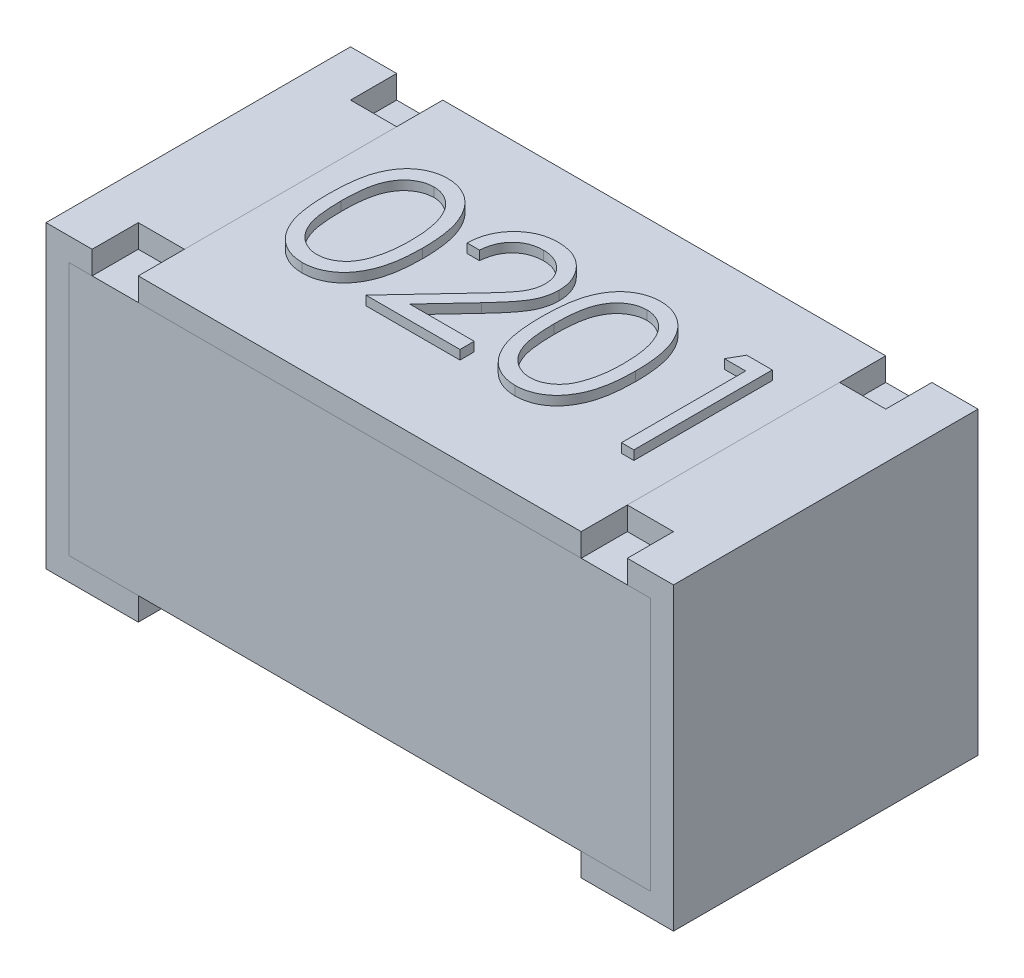
SolidWorks part; units mm, degrees
ref_plane "Front Plane" through (0, 0, 0) normal (0, 0, 1) x (1, 0, 0)
ref_plane "Top Plane" through (0, 0, 0) normal (0, 1, 0) x (1, 0, 0)
ref_plane "Right Plane" through (0, 0, 0) normal (1, 0, 0) x (0, 0, -1)
sketch "Croquis1" plane through (0, 0, 0) normal (0, 1, 0) x (1, 0, 0)
  line L1 (0.315, 0.165) -> (-0.315, 0.165)
  line L2 (0.315, 0.165) -> (0.315, -0.165)
  line L3 (0.315, -0.165) -> (-0.315, -0.165)
  line L4 (-0.315, 0.165) -> (-0.315, -0.165)
  line L5 (0.315, 0.165) -> (-0.315, -0.165) construction
  line L6 (0.315, -0.165) -> (-0.315, 0.165) construction
  point P0 (0, 0)
  dimension "D1" = 0.33
  dimension "D2" = 0.63
extrude "Extruir1" add sketch "Croquis1" along normal blind 0.3
sketch "Croquis2" plane through (0, 0, 0.165) normal (0, 0, 1) x (1, 0, 0)
  line L0 (0.315, 0.3) -> (0.315, 0) construction
  line L1 (-0.315, 0) -> (0.315, 0)
  line L2 (-0.315, 0) -> (-0.315, 0.025)
  line L3 (-0.315, 0.025) -> (0.315, 0.025)
  line L4 (0.315, 0) -> (0.315, 0.025)
  dimension "D1" = 0.025
extrude "Extruir2" cut sketch "Croquis2" against normal through all
sketch "Croquis3" plane through (0, 0, 0.165) normal (0, 0, 1) x (1, 0, 0)
  line L0 (-0.24, 0.325) -> (-0.34, 0.325)
  line L1 (-0.34, 0.325) -> (-0.34, 0)
  line L2 (-0.34, 0) -> (-0.24, 0)
  line L4 (-0.315, 0.3) -> (-0.315, 0.025) construction
  line L5 (-0.315, 0.3) -> (0.315, 0.3) construction
  dimension "D1" = 0.025
  dimension "D2" = 0.025
  dimension "D3" = 0.1
  dimension "D4" = 0.1
  dimension "D5" = 0.325
sketch3d "Croquis3D1"
  line L0 (-0.24, 0.325, 0.165) -> (-0.24, 0.325, -0.165)
  line L1 (-0.24, 0.325, -0.165) -> (-0.24, 0.3, -0.165)
  line L2 (-0.24, 0.3, -0.165) -> (-0.24, 0.3, 0.165)
  line L3 (-0.24, 0.3, 0.165) -> (-0.24, 0.325, 0.165)
  line L4 (-0.315, 0.3, -0.165) -> (-0.315, 0.3, 0.165) construction
  dimension "D1" = 0.1
sweep "Barrer1" add profiles "Croquis3D1" path "Croquis3"
ref_plane "Plano1" through (0, 0.3, 0.165) normal (1, 0, 0) x (0, 0, -1)
mirror "Simetría1" about plane through (0, 0.3, 0.165) normal (1, 0, 0) of bodies 104
sketch "Croquis4" plane through (-0.24, 0, 0) normal (1, 0, 0) x (0, 0, -1)
  line L1 (-0.165, 0.325) -> (0.165, 0.325)
  line L2 (-0.165, 0.325) -> (-0.165, 0.3)
  line L3 (-0.165, 0.3) -> (0.165, 0.3)
  line L4 (0.165, 0.325) -> (0.165, 0.3)
extrude "Extruir3" add sketch "Croquis4" along normal up to surface (0.48 mm away) separate body up to face at (0.24, 0.3125, 0)
sketch "Croquis5" plane through (0, 0.325, 0) normal (0, 1, 0) x (1, 0, 0)
  line L0 (0, -0.165) -> (0, 0.165) construction
  line L1 (-0.24, -0.165) -> (-0.29, -0.165)
  line L2 (-0.24, -0.165) -> (-0.24, -0.115)
  line L3 (-0.24, -0.115) -> (-0.29, -0.115)
  line L4 (-0.29, -0.165) -> (-0.29, -0.115)
  line L5 (0.24, -0.165) -> (-0.24, -0.165) construction
  line L6 (0.24, 0.165) -> (-0.24, 0.165) construction
  line L7 (-0.24, 0) -> (0.24, 0) construction
  line L8 (-0.24, 0.165) -> (-0.24, -0.165) construction
  line L9 (0.24, 0.165) -> (0.24, -0.165) construction
  line L10 (-0.29, 0.165) -> (-0.29, 0.115)
  line L11 (-0.24, 0.115) -> (-0.29, 0.115)
  line L12 (-0.24, 0.165) -> (-0.24, 0.115)
  line L13 (-0.24, 0.165) -> (-0.29, 0.165)
  line L14 (0.24, 0.165) -> (0.29, 0.165)
  line L15 (0.24, 0.165) -> (0.24, 0.115)
  line L16 (0.24, 0.115) -> (0.29, 0.115)
  line L17 (0.29, 0.165) -> (0.29, 0.115)
  line L18 (0.29, -0.165) -> (0.29, -0.115)
  line L19 (0.24, -0.115) -> (0.29, -0.115)
  line L20 (0.24, -0.165) -> (0.24, -0.115)
  line L21 (0.24, -0.165) -> (0.29, -0.165)
  dimension "D1" = 0.05
  dimension "D2" = 0.05
extrude "Extruir4" cut sketch "Croquis5" against normal up to next (0.025 mm away)
sketch "Sketch1" plane through (0, 0.325, 0) normal (0, 1, 0) x (1, 0, 0)
  text T0 "0201" font "Century Gothic" height 0.15
extrude "Boss-Extrude1" add sketch "Sketch1" along normal blind 0.01
